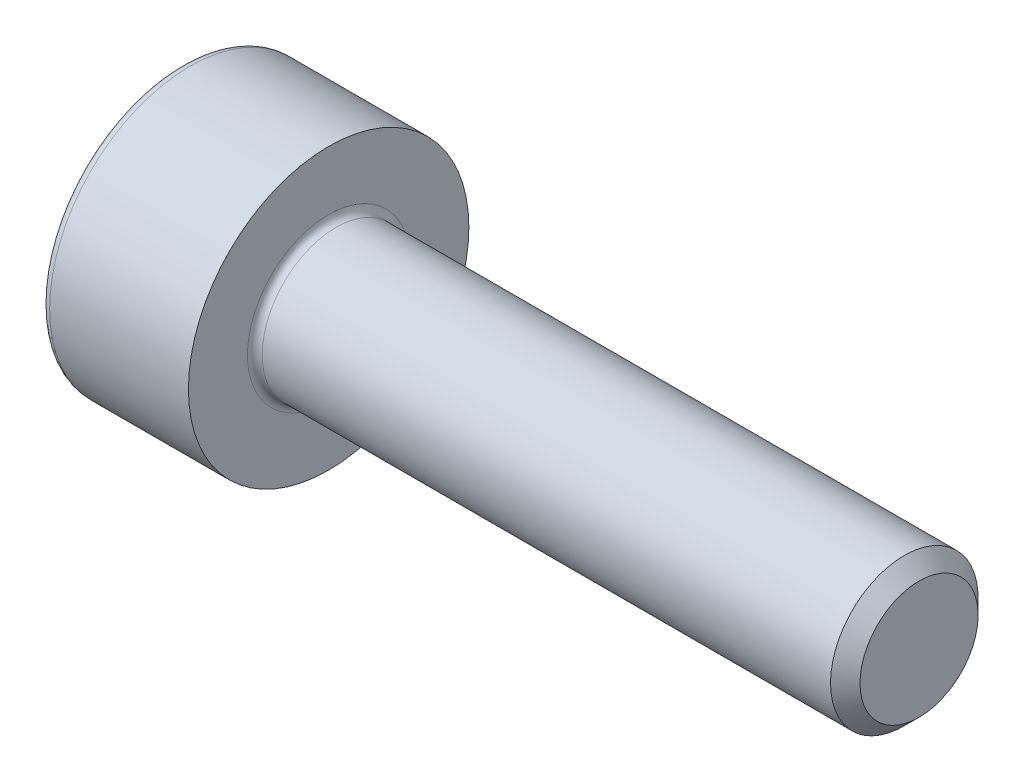
SolidWorks part; units mm, degrees
ref_plane "Front Plane" through (0, 0, 0) normal (0, 0, 1) x (1, 0, 0)
ref_plane "Top Plane" through (0, 0, 0) normal (0, 1, 0) x (1, 0, 0)
ref_plane "Right Plane" through (0, 0, 0) normal (1, 0, 0) x (0, 0, -1)
sketch "Sketch1" plane through (0, 0, 0) normal (0, 0, 1) x (1, 0, 0)
  line L0 (0, 0) -> (0, 1.9)
  line L1 (0, 1.9) -> (2, 1.9)
  line L2 (2, 1.9) -> (2, 0)
  line L3 (0, 0) -> (4.2799, 0) construction
  line L4 (2, 0) -> (10, 0)
  line L5 (10, 0) -> (10, 1)
  line L6 (10, 1) -> (2, 1)
  dimension "D1" = 8
revolve "Revolve1" add sketch "Sketch1" angle 360 about L3
fillet "Fillet1" radius 0.1 1 edges at (2, 0, 1)
fillet "Fillet2" radius 0.12 1 edges at (0, 0, 1.9)
chamfer "Chamfer1" distance 0.2 angle 45 1 edges at (10, 0, 1)
sketch "Sketch2" plane through (0, 0, 0) normal (-1, 0, 0) x (0, 0, 1)
  line L1 (0, 0.866) -> (-0.75, 0.433)
  line L2 (-0.75, 0.433) -> (-0.75, -0.433)
  line L3 (-0.75, -0.433) -> (0, -0.866)
  line L4 (0, -0.866) -> (0.75, -0.433)
  line L5 (0.75, -0.433) -> (0.75, 0.433)
  line L6 (0.75, 0.433) -> (0, 0.866)
  circle A0 centre (0, 0) radius 0.75 construction
extrude "Extrude1" cut sketch "Sketch2" against normal blind 1
